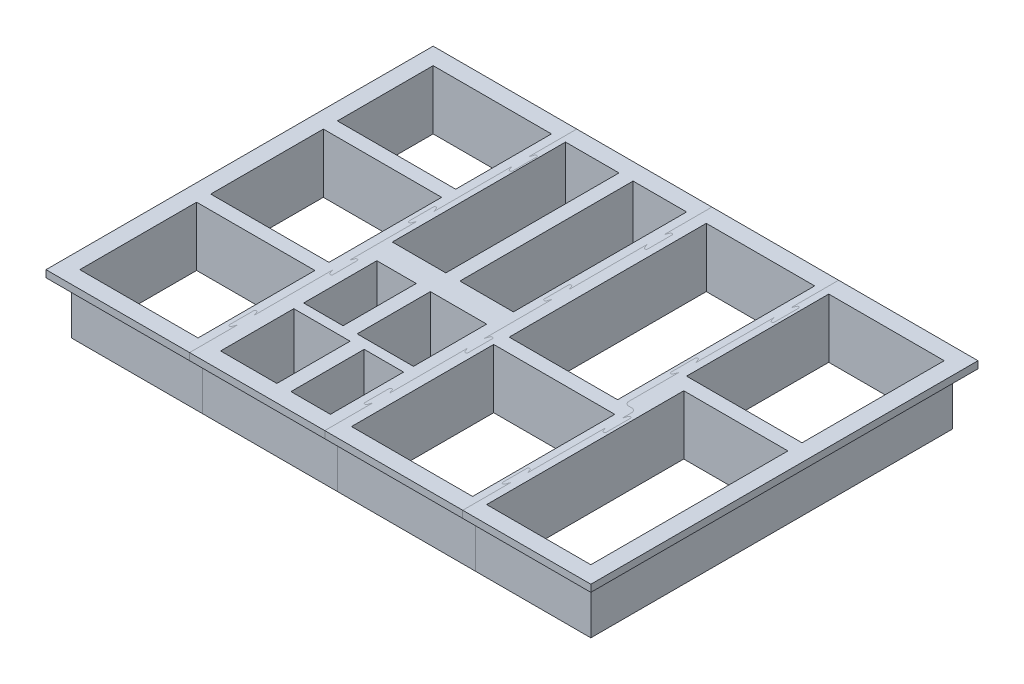
SolidWorks part; units mm, degrees
ref_plane "Front Plane" through (0, 0, 0) normal (0, 0, 1) x (1, 0, 0)
ref_plane "Top Plane" through (0, 0, 0) normal (0, 1, 0) x (1, 0, 0)
ref_plane "Right Plane" through (0, 0, 0) normal (1, 0, 0) x (0, 0, -1)
sketch "Sketch1" plane through (0, 0, 0) normal (0, 1, 0) x (1, 0, 0)
  line L1 (193.5, -137.5) -> (-193.5, -137.5)
  line L2 (193.5, -137.5) -> (193.5, 137.5)
  line L3 (193.5, 137.5) -> (-193.5, 137.5)
  line L4 (-193.5, -137.5) -> (-193.5, 137.5)
  line L5 (193.5, -137.5) -> (-193.5, 137.5) construction
  line L6 (193.5, 137.5) -> (-193.5, -137.5) construction
  point P0 (0, 0)
  dimension "D1" = 387
  dimension "D2" = 275
extrude "Boss-Extrude1" add sketch "Sketch1" along normal blind 47
sketch "Sketch3" plane through (0, 0, 0) normal (0, -1, 0) x (-1, 0, 0)
  line L23 (184.5, -128.5) -> (184.5, 128.5)
  line L24 (184.5, 128.5) -> (-184.5, 128.5)
  line L25 (-184.5, 128.5) -> (-184.5, -128.5)
  line L26 (-184.5, -128.5) -> (184.5, -128.5)
  line L27 (184.5, -128.5) -> (184.5, 128.5)
  line L28 (184.5, 128.5) -> (-184.5, 128.5)
  line L29 (-184.5, 128.5) -> (-184.5, -128.5)
  line L30 (-184.5, -128.5) -> (184.5, -128.5)
  dimension "D1" = 9
extrude "Cut-Extrude2" cut sketch "Sketch3" against normal blind 42 flip side to cut
sketch "Sketch2" plane through (0, 47, 0) normal (0, 1, 0) x (1, 0, 0)
  line L1 (-181.5, -125.5) -> (-97.5, -125.5)
  line L2 (-181.5, -125.5) -> (-181.5, -42.5)
  line L3 (-181.5, -42.5) -> (-97.5, -42.5)
  line L4 (-97.5, -125.5) -> (-97.5, -42.5)
  line L5 (-181.5, -32.5) -> (-97.5, -32.5)
  line L6 (-181.5, -32.5) -> (-181.5, 47.5)
  line L7 (-181.5, 47.5) -> (-97.5, 47.5)
  line L8 (-181.5, 125.5) -> (-181.5, -125.5)
  line L9 (-181.5, -125.5) -> (181.5, -125.5)
  line L10 (181.5, -125.5) -> (181.5, 125.5)
  line L11 (181.5, 125.5) -> (-181.5, 125.5)
  line L12 (-181.5, 125.5) -> (-181.5, -125.5) construction
  line L13 (-181.5, -125.5) -> (181.5, -125.5) construction
  line L14 (181.5, -125.5) -> (181.5, 125.5) construction
  line L15 (181.5, 125.5) -> (-181.5, 125.5) construction
  line L16 (-97.5, -32.5) -> (-97.5, 47.5)
  line L17 (-181.5, 125.5) -> (-97.5, 125.5)
  line L18 (-181.5, 125.5) -> (-181.5, 57.5)
  line L19 (-181.5, 57.5) -> (-97.5, 57.5)
  line L20 (-97.5, 125.5) -> (-97.5, 57.5)
  line L21 (181.5, -125.5) -> (107.5, -125.5)
  line L22 (181.5, -125.5) -> (181.5, 14.5)
  line L23 (181.5, 14.5) -> (107.5, 14.5)
  line L24 (107.5, -125.5) -> (107.5, 14.5)
  line L25 (181.5, 125.5) -> (99.5, 125.5)
  line L26 (181.5, 125.5) -> (181.5, 24.5)
  line L27 (181.5, 24.5) -> (99.5, 24.5)
  line L28 (99.5, 125.5) -> (99.5, 24.5)
  line L29 (89.5, 125.5) -> (12.5, 125.5)
  line L30 (89.5, 125.5) -> (89.5, -14.5)
  line L31 (89.5, -14.5) -> (12.5, -14.5)
  line L32 (12.5, 125.5) -> (12.5, -14.5)
  line L33 (-1.5, 125.5) -> (-39.5, 125.5)
  line L34 (-1.5, 125.5) -> (-1.5, 2.5)
  line L35 (-1.5, 2.5) -> (-39.5, 2.5)
  line L36 (-39.5, 125.5) -> (-39.5, 2.5)
  line L37 (-49.5, 125.5) -> (-87.5, 125.5)
  line L38 (-49.5, 125.5) -> (-49.5, 2.5)
  line L39 (-49.5, 2.5) -> (-87.5, 2.5)
  line L40 (-87.5, 125.5) -> (-87.5, 2.5)
  line L41 (-81.5, -14.5) -> (-53.5, -14.5)
  line L42 (-81.5, -14.5) -> (-81.5, -66.5)
  line L43 (-81.5, -66.5) -> (-53.5, -66.5)
  line L44 (-53.5, -14.5) -> (-53.5, -66.5)
  line L45 (-81.5, -125.5) -> (-41.5, -125.5)
  line L46 (-81.5, -125.5) -> (-81.5, -73.5)
  line L47 (-81.5, -73.5) -> (-41.5, -73.5)
  line L48 (-41.5, -125.5) -> (-41.5, -73.5)
  line L49 (-43.5, -14.5) -> (-3.5, -14.5)
  line L50 (-43.5, -14.5) -> (-43.5, -66.5)
  line L51 (-43.5, -66.5) -> (-3.5, -66.5)
  line L52 (-3.5, -14.5) -> (-3.5, -66.5)
  line L53 (-31.5, -73.5) -> (-3.5, -73.5)
  line L54 (-31.5, -73.5) -> (-31.5, -125.5)
  line L55 (-31.5, -125.5) -> (-3.5, -125.5)
  line L56 (-3.5, -73.5) -> (-3.5, -125.5)
  line L57 (97.5, -125.5) -> (11.5, -125.5)
  line L58 (97.5, -125.5) -> (97.5, -24.5)
  line L59 (97.5, -24.5) -> (11.5, -24.5)
  line L60 (11.5, -125.5) -> (11.5, -24.5)
  dimension "D2" = 74
  dimension "D3" = 82
  dimension "D4" = 101
  dimension "D5" = 10
  dimension "D6" = 86
  dimension "D7" = 10
  dimension "D8" = 15
  dimension "D9" = 28
  dimension "D10" = 40
  dimension "D11" = 52
  dimension "D12" = 52
  dimension "D13" = 77
  dimension "D14" = 38
  dimension "D15" = 38
  dimension "D16" = 84
  dimension "D17" = 68
  dimension "D18" = 80
  dimension "D19" = 10
  dimension "D20" = 10
  dimension "D21" = 7
  dimension "D22" = 10
  dimension "D23" = 101
  dimension "D24" = 10
  dimension "D25" = 10
  dimension "D26" = 123
  dimension "D27" = 10
  dimension "D28" = 10
  dimension "D29" = 40
  dimension "D30" = 10
  dimension "D1" = 12
extrude "Cut-Extrude3" cut sketch "Sketch2" against normal blind 43
sketch "Sketch4" plane through (0, 0, 0) normal (0, -1, 0) x (1, 0, 0)
  line L0 (-81.5, 14.5) -> (-53.5, 14.5) construction
  line L1 (-88.5, 13.5) -> (3.5, 13.5)
  line L2 (-88.5, 13.5) -> (-88.5, 0)
  line L3 (-88.5, 0) -> (3.5, 0)
  line L4 (3.5, 13.5) -> (3.5, 0)
  line L5 (-81.5, 14.5) -> (-81.5, 66.5) construction
  line L6 (-3.5, 14.5) -> (-3.5, 66.5) construction
  dimension "D1" = 1
  dimension "D2" = 7
  dimension "D3" = 7
  dimension "D4" = 13.5
extrude "Cut-Extrude4" cut sketch "Sketch4" against normal blind 35
sketch "Sketch6" plane through (0, 47, 0) normal (0, 1, 0) x (1, 0, 0)
  line L0 (-91.5, 137.5) -> (-91.5, 103.5)
  line L1 (-91.5, -91.5) -> (-92.5603, -88.5868)
  line L2 (-94.5, -88.9288) -> (-94.5, -106.0712)
  line L3 (-92.5603, -106.4132) -> (-91.5, -103.5)
  line L4 (-94.5, 38.5712) -> (-94.5, 21.4288)
  line L5 (-196.8373, 0) -> (245.9069, 0) construction
  line L6 (-91.5, 36) -> (-92.5603, 38.9132)
  line L7 (-90.4397, 88.5868) -> (-91.5, 91.5)
  line L8 (-88.5, 106.0712) -> (-88.5, 88.9288)
  line L9 (-91.5, -24) -> (-90.4397, -21.0868)
  line L10 (-88.5, -21.4288) -> (-88.5, -38.5712)
  line L11 (-90.4397, -38.9132) -> (-91.5, -36)
  line L12 (-91.5, 103.5) -> (-90.4397, 106.4132)
  line L13 (-92.5603, 21.0868) -> (-91.5, 24)
  line L14 (-91.5, 91.5) -> (-91.5, 36)
  line L15 (-91.5, 24) -> (-91.5, -24)
  line L16 (-91.5, -36) -> (-91.5, -91.5)
  line L17 (-91.5, -103.5) -> (-91.5, -137.5)
  line L18 (4.5, 159.547) -> (4.5, -165.453) construction
  line L19 (94.5, 152.4626) -> (94.5, -14.5) construction
  line L20 (94.5, -14.5) -> (102.5, -14.5) construction
  line L21 (102.5, -14.5) -> (102.5, -153.8093) construction
  line L22 (89.5, -14.5) -> (12.5, -14.5) construction
  line L23 (99.5, 125.5) -> (99.5, 24.5) construction
  line L24 (-193.5, -137.5) -> (193.5, -137.5) construction
  line L25 (4.5, -103.5) -> (4.5, -137.5)
  line L26 (3.4397, -106.4132) -> (4.5, -103.5)
  line L27 (1.5, -88.9288) -> (1.5, -106.0712)
  line L28 (4.5, -91.5) -> (3.4397, -88.5868)
  line L29 (4.5, -36) -> (4.5, -91.5)
  line L30 (5.5603, -38.9132) -> (4.5, -36)
  line L31 (7.5, -21.4288) -> (7.5, -38.5712)
  line L32 (4.5, -24) -> (5.5603, -21.0868)
  line L33 (4.5, 24) -> (4.5, -24)
  line L34 (4.5, 36) -> (3.4397, 38.9132)
  line L35 (1.5, 38.5712) -> (1.5, 21.4288)
  line L36 (3.4397, 21.0868) -> (4.5, 24)
  line L37 (4.5, 91.5) -> (4.5, 36)
  line L38 (5.5603, 88.5868) -> (4.5, 91.5)
  line L39 (7.5, 106.0712) -> (7.5, 88.9288)
  line L40 (4.5, 103.5) -> (5.5603, 106.4132)
  line L41 (4.5, 137.5) -> (4.5, 103.5)
  line L42 (102.5, -103.5) -> (102.5, -137.5)
  line L43 (101.4397, -106.4132) -> (102.5, -103.5)
  line L44 (99.5, -88.9288) -> (99.5, -106.0712)
  line L45 (102.5, -36) -> (102.5, -91.5)
  line L46 (102.5, -91.5) -> (101.4397, -88.5868)
  line L47 (103.5603, -38.9132) -> (102.5, -36)
  line L48 (105.5, -21.4288) -> (105.5, -38.5712)
  line L49 (102.5, -24) -> (103.5603, -21.0868)
  line L50 (94.5, 137.5) -> (94.5, 103.5)
  line L51 (94.5, 103.5) -> (95.5603, 106.4132)
  line L52 (97.5, 106.0712) -> (97.5, 88.9288)
  line L53 (95.5603, 88.5868) -> (94.5, 91.5)
  line L54 (94.5, 91.5) -> (94.5, 36)
  line L55 (94.5, 36) -> (93.4397, 38.9132)
  line L56 (91.5, 38.5712) -> (91.5, 21.4288)
  line L57 (93.4397, 21.0868) -> (94.5, 24)
  line L58 (94.5, 24) -> (94.5, -11.5)
  line L59 (107.5, -125.5) -> (107.5, 14.5) construction
  line L60 (11.5, -125.5) -> (11.5, -24.5) construction
  line L61 (-181.5, 125.5) -> (-181.5, 57.5) construction
  line L62 (-97.5, 125.5) -> (-181.5, 125.5) construction
  line L63 (-81.5, -125.5) -> (-81.5, -73.5) construction
  line L64 (193.5, 137.5) -> (-193.5, 137.5) construction
  line L65 (97.5, -14.5) -> (99.5, -14.5)
  line L66 (102.5, -17.5) -> (102.5, -24)
  arc A0 (-92.5603, -106.4132) -> (-94.5, -106.0712) centre (-93.5, -106.0712) cw
  arc A1 (-94.5, -88.9288) -> (-92.5603, -88.5868) centre (-93.5, -88.9288) cw
  arc A2 (-88.5, -21.4288) -> (-90.4397, -21.0868) centre (-89.5, -21.4288) ccw
  arc A3 (-90.4397, -38.9132) -> (-88.5, -38.5712) centre (-89.5, -38.5712) ccw
  arc A4 (-90.4397, 88.5868) -> (-88.5, 88.9288) centre (-89.5, 88.9288) ccw
  arc A5 (-88.5, 106.0712) -> (-90.4397, 106.4132) centre (-89.5, 106.0712) ccw
  arc A6 (-94.5, 38.5712) -> (-92.5603, 38.9132) centre (-93.5, 38.5712) cw
  arc A7 (-92.5603, 21.0868) -> (-94.5, 21.4288) centre (-93.5, 21.4288) cw
  arc A8 (3.4397, -106.4132) -> (1.5, -106.0712) centre (2.5, -106.0712) cw
  arc A9 (1.5, -88.9288) -> (3.4397, -88.5868) centre (2.5, -88.9288) cw
  arc A10 (5.5603, -38.9132) -> (7.5, -38.5712) centre (6.5, -38.5712) ccw
  arc A11 (7.5, -21.4288) -> (5.5603, -21.0868) centre (6.5, -21.4288) ccw
  arc A12 (1.5, 38.5712) -> (3.4397, 38.9132) centre (2.5, 38.5712) cw
  arc A13 (3.4397, 21.0868) -> (1.5, 21.4288) centre (2.5, 21.4288) cw
  arc A14 (5.5603, 88.5868) -> (7.5, 88.9288) centre (6.5, 88.9288) ccw
  arc A15 (7.5, 106.0712) -> (5.5603, 106.4132) centre (6.5, 106.0712) ccw
  arc A16 (101.4397, -106.4132) -> (99.5, -106.0712) centre (100.5, -106.0712) cw
  arc A17 (99.5, -88.9288) -> (101.4397, -88.5868) centre (100.5, -88.9288) cw
  arc A18 (103.5603, -38.9132) -> (105.5, -38.5712) centre (104.5, -38.5712) ccw
  arc A19 (105.5, -21.4288) -> (103.5603, -21.0868) centre (104.5, -21.4288) ccw
  arc A20 (97.5, 106.0712) -> (95.5603, 106.4132) centre (96.5, 106.0712) ccw
  arc A21 (95.5603, 88.5868) -> (97.5, 88.9288) centre (96.5, 88.9288) ccw
  arc A22 (91.5, 38.5712) -> (93.4397, 38.9132) centre (92.5, 38.5712) cw
  arc A23 (93.4397, 21.0868) -> (91.5, 21.4288) centre (92.5, 21.4288) cw
  arc A24 (97.5, -14.5) -> (94.5, -11.5) centre (97.5, -11.5) cw
  arc A25 (102.5, -17.5) -> (99.5, -14.5) centre (99.5, -17.5) ccw
  point P54 (-90.9698, 104.9566)
  point P122 (-91.5, 0)
  dimension "D3" = 1
  dimension "D4" = 1
  dimension "D5" = 1
  dimension "D6" = 1
  dimension "D18" = 1
  dimension "D19" = 1
  dimension "D20" = 1
  dimension "D21" = 1
  dimension "D8" = 0
  dimension "D26" = 137.5
  dimension "D34" = 20
  dimension "D36" = 0.5302
  dimension "D44" = 3
  dimension "D45" = 3
  dimension "D2" = 34
  dimension "D7" = 24
  dimension "D9" = 5
  dimension "D10" = 7
  dimension "D11" = 55.5
  dimension "D12" = 10
  dimension "D13" = 12
  dimension "D14" = 3
  dimension "D15" = 3
  dimension "D16" = 3
  dimension "D17" = 12
  dimension "D22" = 12
  dimension "D23" = 3
  dimension "D24" = 0
  dimension "D25" = 5
  dimension "D27" = 20
  dimension "D28" = 20
  dimension "D29" = 20
  dimension "D30" = 20
  dimension "D31" = 12
  dimension "D32" = 20
  dimension "D33" = 20
  dimension "D35" = 20
  dimension "D37" = 34
  dimension "D38" = 2
  dimension "D39" = 7
  dimension "D40" = 2
  dimension "D41" = 5
  dimension "D42" = 2
  dimension "D43" = 5
split "Split1" trim tools "Sketch6" bodies to split 117 resulting bodies 118 119 120 121
sketch "Sketch8" plane through (-184.5, 0, 0) normal (-1, 0, 0) x (0, 0, 1)
  line L0 (128.5, 42) -> (128.5, 0) construction
  line L1 (-128.5, 0) -> (128.5, 0)
  line L2 (-128.5, 0) -> (-128.5, 5)
  line L3 (-128.5, 5) -> (128.5, 5)
  line L4 (128.5, 0) -> (128.5, 5)
  dimension "D1" = 5
extrude "Cut-Extrude5" cut sketch "Sketch8" against normal through all
